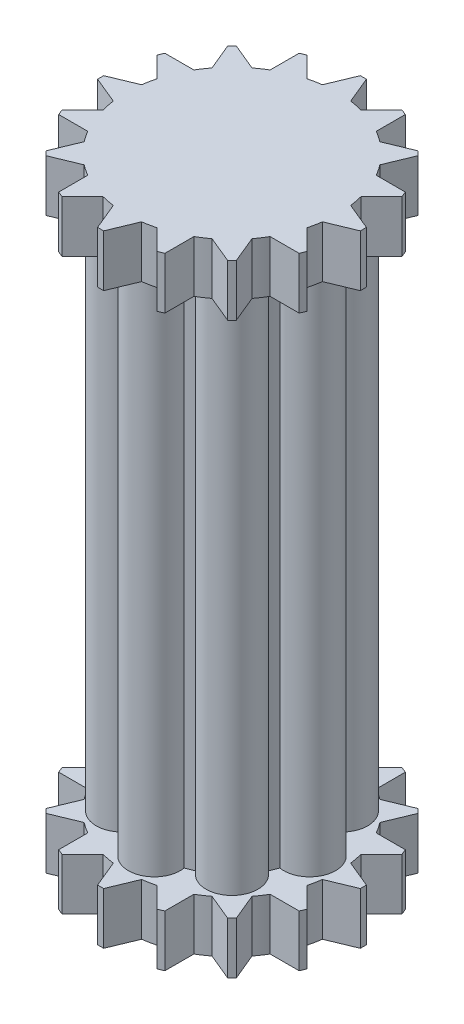
SolidWorks part; units mm, degrees
ref_plane "Front Plane" through (0, 0, 0) normal (1, 0, 0) x (0, 1, 0)
ref_plane "Top Plane" through (0, 0, 0) normal (0, 0, 1) x (0, 1, 0)
ref_plane "Right Plane" through (0, 0, 0) normal (0, 1, 0) x (-1, 0, 0)
sketch "Sketch2" plane through (0, 0, 0) normal (0, 1, 0) x (-1, 0, 0)
  arc A0 (-19.1067, 23.1286) -> (-19.4594, 22.8327) centre (0, 0) ccw
  arc A1 (29.5833, 4.9826) -> (29.5833, -4.9826) centre (30, 0) cw
  arc A2 (29.5034, -5.436) -> (26.0951, -14.8002) centre (28.1908, -10.2606) cw
  arc A3 (25.8649, -15.1989) -> (19.4594, -22.8327) centre (22.9813, -19.2836) cw
  arc A4 (19.1067, -23.1286) -> (10.4766, -28.1112) centre (15, -25.9808) cw
  arc A5 (10.044, -28.2687) -> (0.2302, -29.9991) centre (5.2094, -29.5442) cw
  arc A6 (-0.2302, -29.9991) -> (-10.044, -28.2687) centre (-5.2094, -29.5442) cw
  arc A7 (-10.4766, -28.1112) -> (-19.1067, -23.1286) centre (-15, -25.9808) cw
  arc A8 (-19.4594, -22.8327) -> (-25.8649, -15.1989) centre (-22.9813, -19.2836) cw
  arc A9 (-26.0951, -14.8002) -> (-29.5034, -5.436) centre (-28.1908, -10.2606) cw
  arc A10 (-29.5833, -4.9826) -> (-29.5833, 4.9826) centre (-30, 0) cw
  arc A11 (-29.5034, 5.436) -> (-26.0951, 14.8002) centre (-28.1908, 10.2606) cw
  arc A12 (-25.8649, 15.1989) -> (-19.4594, 22.8327) centre (-22.9813, 19.2836) cw
  arc A13 (-19.1067, 23.1286) -> (-10.4766, 28.1112) centre (-15, 25.9808) cw
  arc A14 (-10.044, 28.2687) -> (-0.2302, 29.9991) centre (-5.2094, 29.5442) cw
  arc A15 (0.2302, 29.9991) -> (10.044, 28.2687) centre (5.2094, 29.5442) cw
  arc A16 (10.4766, 28.1112) -> (19.1067, 23.1286) centre (15, 25.9808) cw
  arc A17 (19.4594, 22.8327) -> (25.8649, 15.1989) centre (22.9813, 19.2836) cw
  arc A18 (26.0951, 14.8002) -> (29.5034, 5.436) centre (28.1908, 10.2606) cw
  arc A19 (-10.044, 28.2687) -> (-10.4766, 28.1112) centre (0, 0) ccw
  arc A20 (0.2302, 29.9991) -> (-0.2302, 29.9991) centre (0, 0) ccw
  arc A21 (10.4766, 28.1112) -> (10.044, 28.2687) centre (0, 0) ccw
  arc A22 (19.4594, 22.8327) -> (19.1067, 23.1286) centre (0, 0) ccw
  arc A23 (26.0951, 14.8002) -> (25.8649, 15.1989) centre (0, 0) ccw
  arc A24 (29.5833, 4.9826) -> (29.5034, 5.436) centre (0, 0) ccw
  arc A25 (29.5034, -5.436) -> (29.5833, -4.9826) centre (0, 0) ccw
  arc A26 (25.8649, -15.1989) -> (26.0951, -14.8002) centre (0, 0) ccw
  arc A27 (19.1067, -23.1286) -> (19.4594, -22.8327) centre (0, 0) ccw
  arc A28 (10.044, -28.2687) -> (10.4766, -28.1112) centre (0, 0) ccw
  arc A29 (-0.2302, -29.9991) -> (0.2302, -29.9991) centre (0, 0) ccw
  arc A30 (-10.4766, -28.1112) -> (-10.044, -28.2687) centre (0, 0) ccw
  arc A31 (-19.4594, -22.8327) -> (-19.1067, -23.1286) centre (0, 0) ccw
  arc A32 (-26.0951, -14.8002) -> (-25.8649, -15.1989) centre (0, 0) ccw
  arc A33 (-29.5833, -4.9826) -> (-29.5034, -5.436) centre (0, 0) ccw
  arc A34 (-29.5034, 5.436) -> (-29.5833, 4.9826) centre (0, 0) ccw
  arc A35 (-25.8649, 15.1989) -> (-26.0951, 14.8002) centre (0, 0) ccw
  circle A36 centre (0, 0) radius 15 construction
  arc A37 (14.1667, 4.9301) -> (14.1667, -4.9301) centre (15, 0) cw
  arc A38 (13.5034, -6.5313) -> (6.5313, -13.5034) centre (10.6066, -10.6066) cw
  arc A39 (4.9301, -14.1667) -> (-4.9301, -14.1667) centre (0, -15) cw
  arc A40 (-6.5313, -13.5034) -> (-13.5034, -6.5313) centre (-10.6066, -10.6066) cw
  arc A41 (-14.1667, -4.9301) -> (-14.1667, 4.9301) centre (-15, 0) cw
  arc A42 (-13.5034, 6.5313) -> (-6.5313, 13.5034) centre (-10.6066, 10.6066) cw
  arc A43 (-4.9301, 14.1667) -> (4.9301, 14.1667) centre (0, 15) cw
  arc A44 (6.5313, 13.5034) -> (13.5034, 6.5313) centre (10.6066, 10.6066) cw
  arc A45 (-13.5034, 6.5313) -> (-14.1667, 4.9301) centre (0, 0) ccw
  arc A46 (-4.9301, 14.1667) -> (-6.5313, 13.5034) centre (0, 0) ccw
  arc A47 (6.5313, 13.5034) -> (4.9301, 14.1667) centre (0, 0) ccw
  arc A48 (14.1667, 4.9301) -> (13.5034, 6.5313) centre (0, 0) ccw
  arc A49 (13.5034, -6.5313) -> (14.1667, -4.9301) centre (0, 0) ccw
  arc A50 (4.9301, -14.1667) -> (6.5313, -13.5034) centre (0, 0) ccw
  arc A51 (-6.5313, -13.5034) -> (-4.9301, -14.1667) centre (0, 0) ccw
  arc A52 (-14.1667, -4.9301) -> (-13.5034, -6.5313) centre (0, 0) ccw
  point P60 (0, 0)
  point P84 (0, 0)
  dimension "D1" = 60
  dimension "D2" = 5
  dimension "D4" = 30
  dimension "D6" = 5
  dimension "D3" = 18
  dimension "D5" = 8
extrude "Boss-Extrude2" add sketch "Sketch2" along normal blind 100 contours A42 A46 A43 A47 A44 A48 A37 A49 A38 A50 A39 A51 A40 A52 A41 A45
sketch "Sketch3" plane through (0, 0, 0) normal (0, -1, 0) x (1, 0, 0)
  line L0 (0, -57.0817) -> (0, 57.0817) construction
  line L1 (0, 25.375) -> (2.1167, 20.2647) construction
  line L2 (0, 25.375) -> (-2.1167, 20.2647) construction
  line L5 (-2.733, 20.1909) -> (2.733, 20.1909) construction
  line L32 (-2.733, 20.1909) -> (-0.5885, 25.3682)
  line L33 (2.733, 20.1909) -> (0.5885, 25.3682)
  line L34 (5.2017, 19.6998) -> (9.1643, 23.6623)
  line L35 (10.2517, 17.6081) -> (10.2517, 23.2119)
  line L36 (12.3446, 16.2096) -> (17.5219, 18.3541)
  line L37 (16.2096, 12.3446) -> (18.3541, 17.5219)
  line L38 (17.6081, 10.2517) -> (23.2119, 10.2517)
  line L39 (19.6998, 5.2017) -> (23.6623, 9.1643)
  line L40 (20.1909, 2.733) -> (25.3682, 0.5885)
  line L41 (20.1909, -2.733) -> (25.3682, -0.5885)
  line L42 (19.6998, -5.2017) -> (23.6623, -9.1643)
  line L43 (17.6081, -10.2517) -> (23.2119, -10.2517)
  line L44 (16.2096, -12.3446) -> (18.3541, -17.5219)
  line L45 (12.3446, -16.2096) -> (17.5219, -18.3541)
  line L46 (10.2517, -17.6081) -> (10.2517, -23.2119)
  line L47 (5.2017, -19.6998) -> (9.1643, -23.6623)
  line L48 (2.733, -20.1909) -> (0.5885, -25.3682)
  line L49 (-2.733, -20.1909) -> (-0.5885, -25.3682)
  line L50 (-5.2017, -19.6998) -> (-9.1643, -23.6623)
  line L51 (-10.2517, -17.6081) -> (-10.2517, -23.2119)
  line L52 (-12.3446, -16.2096) -> (-17.5219, -18.3541)
  line L53 (-16.2096, -12.3446) -> (-18.3541, -17.5219)
  line L54 (-17.6081, -10.2517) -> (-23.2119, -10.2517)
  line L55 (-19.6998, -5.2017) -> (-23.6623, -9.1643)
  line L56 (-20.1909, -2.733) -> (-25.3682, -0.5885)
  line L57 (-20.1909, 2.733) -> (-25.3682, 0.5885)
  line L58 (-19.6998, 5.2017) -> (-23.6623, 9.1643)
  line L59 (-17.6081, 10.2517) -> (-23.2119, 10.2517)
  line L60 (-16.2096, 12.3446) -> (-18.3541, 17.5219)
  line L61 (-12.3446, 16.2096) -> (-17.5219, 18.3541)
  line L62 (-10.2517, 17.6081) -> (-10.2517, 23.2119)
  line L63 (-5.2017, 19.6998) -> (-9.1643, 23.6623)
  arc A28 (-16.2096, 12.3446) -> (-17.6081, 10.2517) centre (0, 0) ccw
  arc A29 (-23.2119, 10.2517) -> (-23.6623, 9.1643) centre (0, 0) ccw
  arc A30 (-17.5219, 18.3541) -> (-18.3541, 17.5219) centre (0, 0) ccw
  arc A31 (-10.2517, 17.6081) -> (-12.3446, 16.2096) centre (0, 0) ccw
  arc A32 (-9.1643, 23.6623) -> (-10.2517, 23.2119) centre (0, 0) ccw
  arc A33 (0.5885, 25.3682) -> (-0.5885, 25.3682) centre (0, 0) ccw
  arc A34 (10.2517, 23.2119) -> (9.1643, 23.6623) centre (0, 0) ccw
  arc A35 (-2.733, 20.1909) -> (-5.2017, 19.6998) centre (0, 0) ccw
  arc A36 (5.2017, 19.6998) -> (2.733, 20.1909) centre (0, 0) ccw
  arc A37 (18.3541, 17.5219) -> (17.5219, 18.3541) centre (0, 0) ccw
  arc A38 (12.3446, 16.2096) -> (10.2517, 17.6081) centre (0, 0) ccw
  arc A39 (17.6081, 10.2517) -> (16.2096, 12.3446) centre (0, 0) ccw
  arc A40 (23.6623, 9.1643) -> (23.2119, 10.2517) centre (0, 0) ccw
  arc A41 (25.3682, -0.5885) -> (25.3682, 0.5885) centre (0, 0) ccw
  arc A42 (23.2119, -10.2517) -> (23.6623, -9.1643) centre (0, 0) ccw
  arc A43 (20.1909, 2.733) -> (19.6998, 5.2017) centre (0, 0) ccw
  arc A44 (19.6998, -5.2017) -> (20.1909, -2.733) centre (0, 0) ccw
  arc A45 (17.5219, -18.3541) -> (18.3541, -17.5219) centre (0, 0) ccw
  arc A46 (9.1643, -23.6623) -> (10.2517, -23.2119) centre (0, 0) ccw
  arc A47 (10.2517, -17.6081) -> (12.3446, -16.2096) centre (0, 0) ccw
  arc A48 (16.2096, -12.3446) -> (17.6081, -10.2517) centre (0, 0) ccw
  arc A49 (-0.5885, -25.3682) -> (0.5885, -25.3682) centre (0, 0) ccw
  arc A50 (-10.2517, -23.2119) -> (-9.1643, -23.6623) centre (0, 0) ccw
  arc A51 (-5.2017, -19.6998) -> (-2.733, -20.1909) centre (0, 0) ccw
  arc A52 (2.733, -20.1909) -> (5.2017, -19.6998) centre (0, 0) ccw
  arc A53 (-18.3541, -17.5219) -> (-17.5219, -18.3541) centre (0, 0) ccw
  arc A54 (-23.6623, -9.1643) -> (-23.2119, -10.2517) centre (0, 0) ccw
  arc A55 (-12.3446, -16.2096) -> (-10.2517, -17.6081) centre (0, 0) ccw
  arc A56 (-17.6081, -10.2517) -> (-16.2096, -12.3446) centre (0, 0) ccw
  arc A57 (-20.1909, -2.733) -> (-19.6998, -5.2017) centre (0, 0) ccw
  arc A58 (-25.3682, 0.5885) -> (-25.3682, -0.5885) centre (0, 0) ccw
  arc A59 (-19.6998, 5.2017) -> (-20.1909, 2.733) centre (0, 0) ccw
  point P13 (0, 57.0817)
  point P17 (0, 47.4976)
  point P78 (0, 0)
  dimension "D2" = 50.75
  dimension "D1" = 40.75
  dimension "D3" = 22.5
  dimension "D4" = 22.5
  dimension "D5" = 5.466
  dimension "D6" = 16
extrude "Boss-Extrude3" add sketch "Sketch3" along normal blind 10
ref_plane "Plane1" through (0, 50, 0) normal (0, 1, 0) x (1, 0, 0)
mirror "Mirror1" about plane through (0, 50, 0) normal (0, 1, 0) of "Boss-Extrude3"
